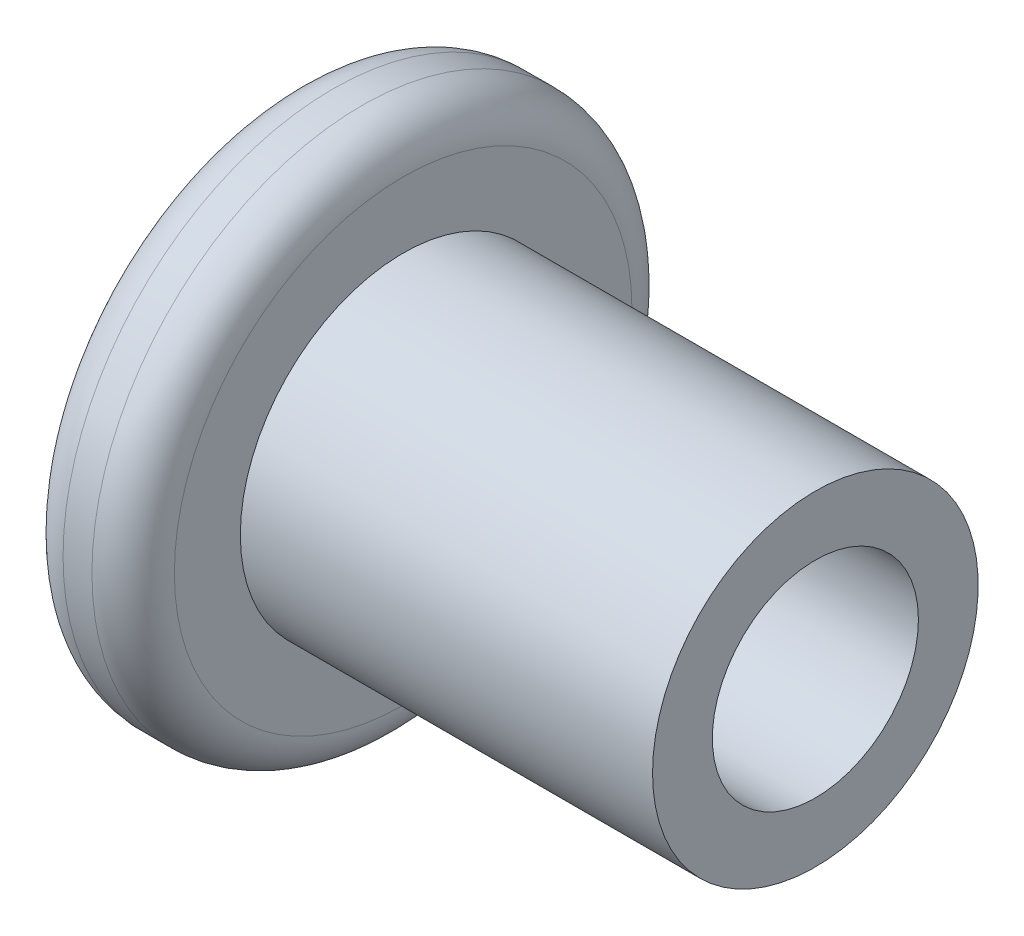
SolidWorks part; units mm, degrees
material "AISI 304"
ref_plane "前视基准面" through (0, 0, 0) normal (0, 0, 1) x (1, 0, 0)
ref_plane "上视基准面" through (0, 0, 0) normal (0, 1, 0) x (1, 0, 0)
ref_plane "右视基准面" through (0, 0, 0) normal (1, 0, 0) x (0, 0, -1)
sketch "草图1" plane through (0, 0, 0) normal (0, 0, 1) x (1, 0, 0)
  line L0 (0, 0) -> (12.7, 0) construction
  line L1 (0, 0) -> (0, 6.55)
  line L2 (0, 6.55) -> (2.7, 6.55)
  line L3 (2.7, 6.55) -> (2.7, 3.95)
  line L4 (2.7, 3.95) -> (12.7, 3.95)
  line L5 (12.7, 3.95) -> (12.7, 0)
  line L6 (0, 0) -> (12.7, 0)
  dimension "D1" = 6.55
  dimension "D2" = 2.7
  dimension "D3" = 7.9
  dimension "D4" = 10
revolve "旋转1" add sketch "草图1" angle 360 about L0
fillet "圆角1" radius 1 2 edges at (2.7, 0, 6.55) (0, 0, 6.55)
sketch "草图2" plane through (0, 0, 0) normal (-1, 0, 0) x (0, 0, 1)
  line L1 (1.1547, 2) -> (-1.1547, 2)
  line L2 (-1.1547, 2) -> (-2.3094, 0)
  line L3 (-2.3094, 0) -> (-1.1547, -2)
  line L4 (-1.1547, -2) -> (1.1547, -2)
  line L5 (1.1547, -2) -> (2.3094, 0)
  line L6 (2.3094, 0) -> (1.1547, 2)
  circle A0 centre (0, 0) radius 2 construction
  dimension "D1" = 4
extrude "切除-拉伸1" cut sketch "草图2" against normal blind 1
hole_wizard "M6 螺纹孔1" positions "草图4" profile "草图5" tap size "M6" standard "GB"
sketch "草图4" plane through (12.7, 0, 0) normal (1, 0, 0) x (0, 0, -1)
  point P0 (0, 0)
sketch "草图5" plane through (12.7, 0, 0) normal (0, 1, 0) x (0, 0, -1)
  line L0 (0, 0) -> (0, 5.6022)
  line L1 (0, 5.6022) -> (2.5, 4.1)
  line L2 (2.5, 4.1) -> (2.5, 0)
  line L5 (2.5, 0) -> (0, 0)
  line L10 (0, 5.6022) -> (-2.5, 4.1) construction
  line L11 (0, -6.35) -> (0, 107.95) construction
  dimension "螺纹孔钻头直径" = 5
  dimension "螺纹孔钻头深度" = 4.1
  dimension "导头角度" = 118
cosmetic thread "孔螺蚊线1" parameters "D1"=5.6, "D2"=6
